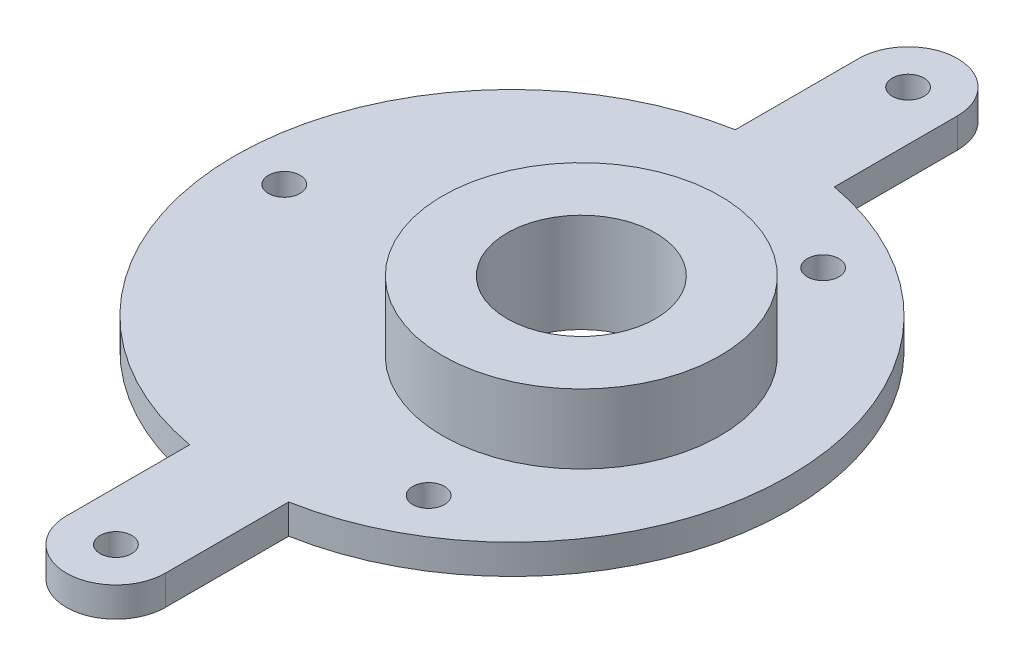
SolidWorks part; units mm, degrees
ref_plane "正面" through (0, 0, 0) normal (0, 0, 1) x (1, 0, 0)
ref_plane "平面" through (0, 0, 0) normal (0, 1, 0) x (1, 0, 0)
ref_plane "右側面" through (0, 0, 0) normal (1, 0, 0) x (0, 0, -1)
sketch "ｽｹｯﾁ1" plane through (0, 0, 0) normal (0, 1, 0) x (1, 0, 0)
  line L0 (0, 40) -> (0, -40) construction
  line L1 (5, 40) -> (5, 27.55)
  line L2 (-5, 40) -> (-5, 27.55)
  line L3 (-5, -27.55) -> (-5, -40)
  line L4 (5, -27.55) -> (5, -40)
  arc A3 (-5, 27.55) -> (-5, -27.55) centre (0, 0) ccw
  arc A4 (5, 40) -> (-5, 40) centre (0, 40) ccw
  arc A5 (-5, -40) -> (5, -40) centre (0, -40) ccw
  arc A6 (5, -27.55) -> (5, 27.55) centre (0, 0) ccw
  circle A7 centre (0, 40) radius 1.6
  circle A8 centre (0, -40) radius 1.6
  point P9 (0, 0)
  point P20 (0, 0)
  dimension "D3" = 3.2
  dimension "D8" = 28
  dimension "D6" = 80
  dimension "D7" = 10
extrude "ﾎﾞｽ - 押し出し1" add sketch "ｽｹｯﾁ1" along normal blind 3
sketch "ｽｹｯﾁ4" plane through (0, 3, 0) normal (0, 1, 0) x (1, 0, 0)
  circle A0 centre (7, 0) radius 14
  dimension "D1" = 28
  dimension "D2" = 7
extrude "ﾎﾞｽ - 押し出し2" add sketch "ｽｹｯﾁ4" along normal blind 7
sketch "ｽｹｯﾁ2" plane through (0, 3, 0) normal (0, 1, 0) x (1, 0, 0)
  circle A0 centre (7, 0) radius 7.5
  dimension "D1" = 15
  dimension "D2" = 7
extrude "ｶｯﾄ - 押し出し1" cut sketch "ｽｹｯﾁ2" against normal through all both and the other way through all
sketch "ｽｹｯﾁ3" plane through (0, 3, 0) normal (0, 1, 0) x (1, 0, 0)
  circle A0 centre (-23, 0) radius 1.6
  circle A1 centre (0, 0) radius 23 construction
  circle A2 centre (11.5, 19.9186) radius 1.6
  circle A3 centre (11.5, -19.9186) radius 1.6
  point P11 (0, 0)
  dimension "D1" = 46
  dimension "D2" = 3.2
  dimension "D3" = 3
extrude "ｶｯﾄ - 押し出し2" cut sketch "ｽｹｯﾁ3" against normal through all
